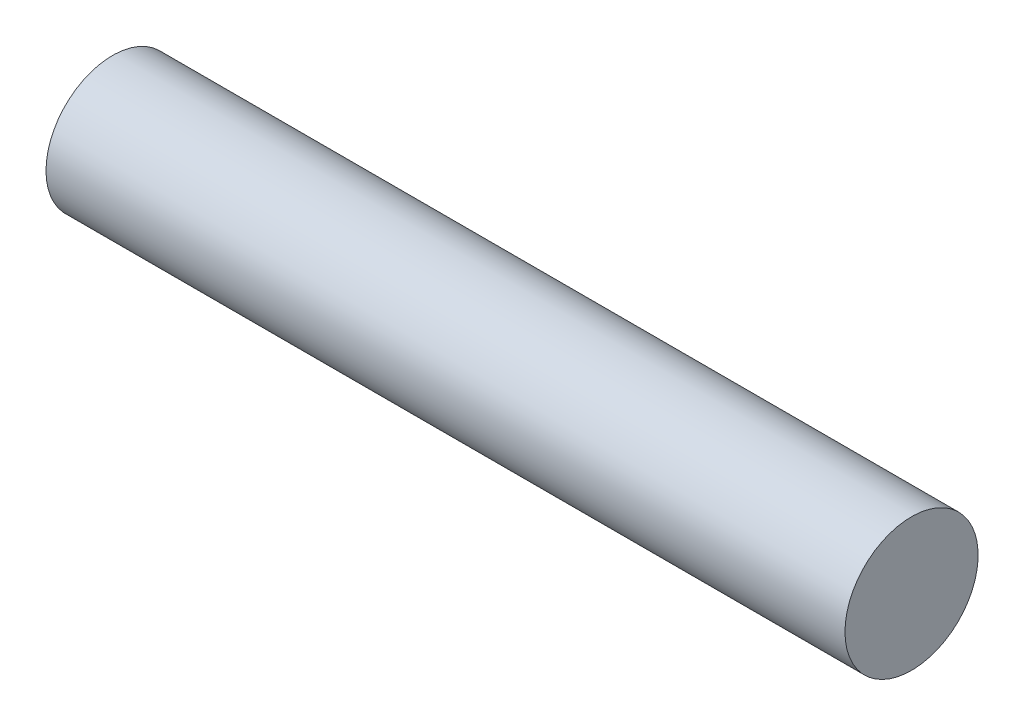
SolidWorks part; units mm, degrees
ref_plane "Front Plane" through (0, 0, 0) normal (0, 0, 1) x (1, 0, 0)
ref_plane "Top Plane" through (0, 0, 0) normal (0, 1, 0) x (1, 0, 0)
ref_plane "Right Plane" through (0, 0, 0) normal (1, 0, 0) x (0, 0, -1)
sketch "Sketch1" plane through (0, 0, 0) normal (1, 0, 0) x (0, 0, -1)
  circle A0 centre (0, 0) radius 3.175
  dimension "D1" = 6.35
extrude "Boss-Extrude1" add sketch "Sketch1" along normal blind 38.1 contours A0
